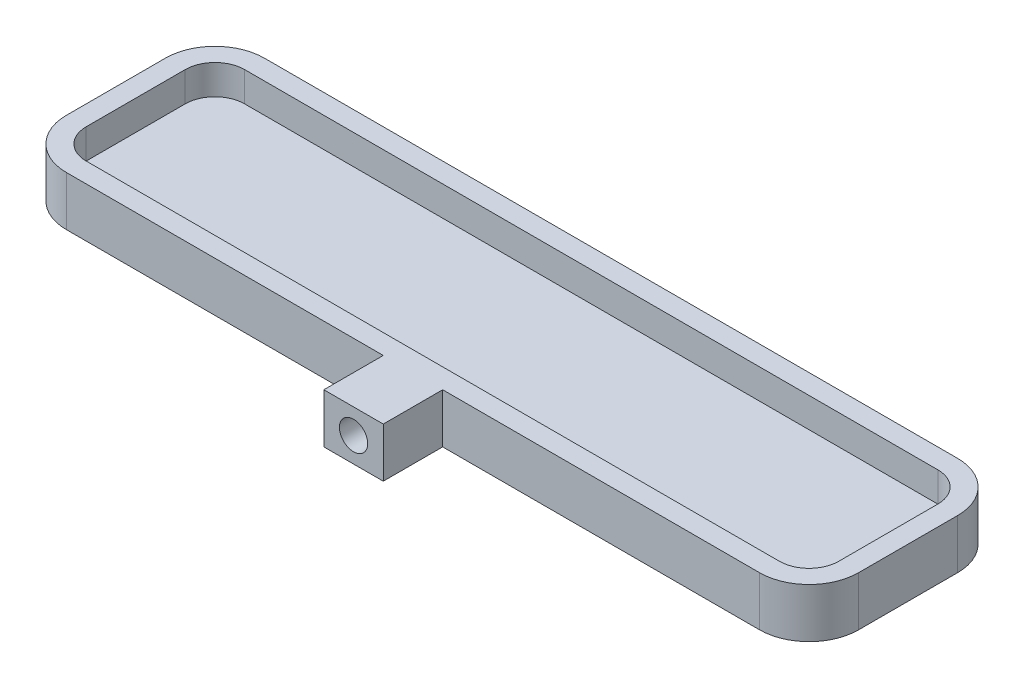
SolidWorks part; units mm, degrees
ref_plane "Front Plane" through (0, 0, 0) normal (0, 0, 1) x (1, 0, 0)
ref_plane "Top Plane" through (0, 0, 0) normal (0, 1, 0) x (1, 0, 0)
ref_plane "Right Plane" through (0, 0, 0) normal (1, 0, 0) x (0, 0, -1)
sketch "Sketch1" plane through (0, 0, 0) normal (0, 1, 0) x (1, 0, 0)
  line L1 (-40, -10) -> (40, -10)
  line L2 (-40, -10) -> (-40, 10)
  line L3 (-40, 10) -> (40, 10)
  line L4 (40, -10) -> (40, 10)
  line L5 (-40, -10) -> (40, 10) construction
  line L6 (-40, 10) -> (40, -10) construction
  point P0 (0, 0)
  dimension "D1" = 80
  dimension "D2" = 20
extrude "Boss-Extrude1" add sketch "Sketch1" along normal blind 5
fillet "Fillet1" radius 5 4 edges at (40, 2.5, -10) (40, 2.5, 10) (-40, 2.5, -10) (-40, 2.5, 10)
shell "Shell1" thickness 2
sketch "Sketch2" plane through (0, 0, 10) normal (0, 0, 1) x (1, 0, 0)
  line L0 (-35, 0) -> (35, 0) construction
  line L1 (-3, 0) -> (3, 0)
  line L2 (-3, 0) -> (-3, 5)
  line L3 (-3, 5) -> (3, 5)
  line L4 (3, 0) -> (3, 5)
  line L5 (-35, 5) -> (35, 5) construction
  line L6 (0, 0) -> (0, 22.961) construction
  dimension "D1" = 6
  dimension "D2" = 5
extrude "Boss-Extrude2" add sketch "Sketch2" along normal blind 6
sketch "Sketch3" plane through (0, 0, 16) normal (0, 0, 1) x (1, 0, 0)
  line L0 (3, 5) -> (-3, 5) construction
  line L1 (-3, 5) -> (-3, 0) construction
  circle A0 centre (0, 2.5) radius 1.425
  dimension "D1" = 2.85
  dimension "D2" = 2.5
  dimension "D3" = 3
extrude "Cut-Extrude1" cut sketch "Sketch3" against normal blind 4
